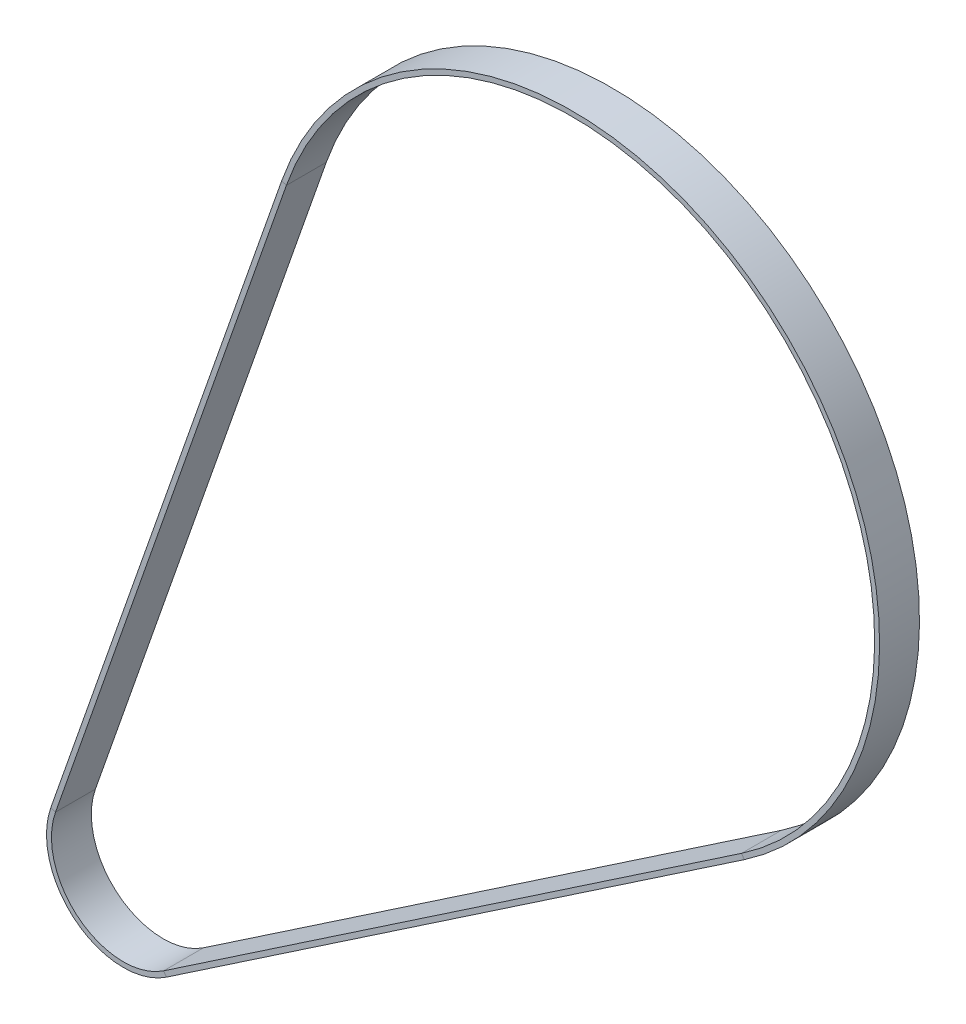
SolidWorks part; units mm, degrees
ref_plane "Front Plane" through (0, 0, 0) normal (0, 0, 1) x (1, 0, 0)
ref_plane "Top Plane" through (0, 0, 0) normal (0, 1, 0) x (1, 0, 0)
ref_plane "Right Plane" through (0, 0, 0) normal (1, 0, 0) x (0, 0, -1)
sketch "Sketch2" plane through (0, 0, 0) normal (0, 0, 1) x (1, 0, 0)
  line L0 (0, 0) -> (1, 0) construction
  line L1 (0, 0) -> (0, 1) construction
  line L2 (17.2485, -25.5132) -> (-41.0614, -64.9341)
  line L3 (-52.3568, -56.225) -> (-29.0609, 10.193)
  arc A0 (-29.0609, 10.193) -> (17.2485, -25.5132) centre (0, 0) cw
  arc A1 (-41.0614, -64.9341) -> (-52.3568, -56.225) centre (-45.2685, -58.7112) cw
ref_plane "Plane1" through (-52.3568, -56.225, 0) normal (0.331, 0.9436, 0) x (0.9436, -0.331, 0)
sketch "Sketch3" plane through (-52.3568, -56.225, 0) normal (0.331, 0.9436, 0) x (0.9436, -0.331, 0)
  line L0 (0, 0) -> (13.5413, 0) construction
  line L1 (-0.2432, 2.0118) -> (0.2568, 2.0118)
  line L2 (-0.2432, 2.0118) -> (-0.2432, -2.0118)
  line L3 (-0.2432, -2.0118) -> (0.2568, -2.0118)
  line L4 (0.2568, 2.0118) -> (0.2568, -2.0118)
  line L5 (0.0068, 2.0118) -> (0.0068, -2.0118) construction
  point P4 (0.2568, 0)
  dimension "D1" = 4.0237
  dimension "D2" = 0.5
sweep "Sweep1" add profiles "Sketch3" path "Sketch2"
